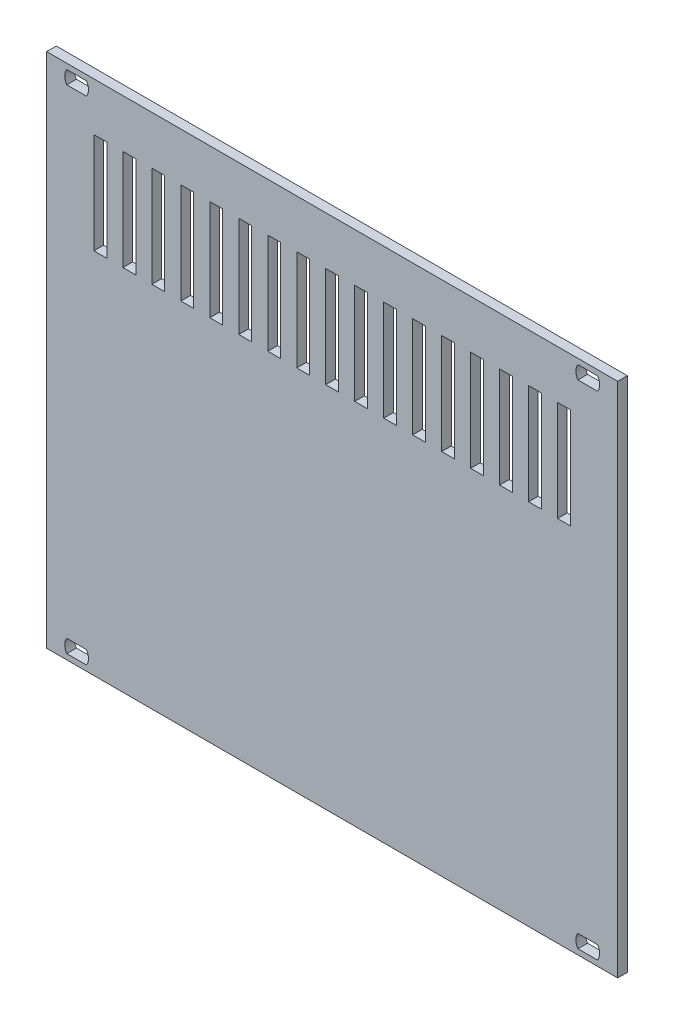
SolidWorks part; units mm, degrees
material "Alliage 1060"
ref_plane "Plan de face" through (0, 0, 0) normal (0, 0, 1) x (1, 0, 0)
ref_plane "Plan de dessus" through (0, 0, 0) normal (0, 1, 0) x (1, 0, 0)
ref_plane "Plan de droite" through (0, 0, 0) normal (1, 0, 0) x (0, 0, -1)
sketch "Model" plane through (0, 0, 0) normal (0, 0, 1) x (1, 0, 0)
  line L0 (141.9, 128.4) -> (141.9, 0)
  line L1 (0, 128.4) -> (141.9, 128.4)
  line L2 (0, 0) -> (0, 128.4)
  line L3 (141.9, 0) -> (0, 0)
  line L4 (9.8954, 123.75) -> (5.0046, 123.75)
  line L5 (5.0046, 127.05) -> (9.8954, 127.05)
  line L6 (9.8954, 1.35) -> (5.0046, 1.35)
  line L7 (5.0046, 4.65) -> (9.8954, 4.65)
  line L8 (136.8954, 123.75) -> (132.0046, 123.75)
  line L9 (132.0046, 127.05) -> (136.8954, 127.05)
  line L10 (136.8954, 1.35) -> (132.0046, 1.35)
  line L11 (132.0046, 4.65) -> (136.8954, 4.65)
  line L12 (14.95, 116.4) -> (14.95, 91.4)
  line L13 (14.95, 91.4) -> (11.75, 91.4)
  line L14 (11.75, 91.4) -> (11.75, 116.4)
  line L15 (11.75, 116.4) -> (14.95, 116.4)
  line L16 (22.15, 116.4) -> (22.15, 91.4)
  line L17 (22.15, 91.4) -> (18.95, 91.4)
  line L18 (18.95, 91.4) -> (18.95, 116.4)
  line L19 (18.95, 116.4) -> (22.15, 116.4)
  line L20 (29.35, 116.4) -> (29.35, 91.4)
  line L21 (29.35, 91.4) -> (26.15, 91.4)
  line L22 (26.15, 91.4) -> (26.15, 116.4)
  line L23 (26.15, 116.4) -> (29.35, 116.4)
  line L24 (36.55, 116.4) -> (36.55, 91.4)
  line L25 (36.55, 91.4) -> (33.35, 91.4)
  line L26 (33.35, 91.4) -> (33.35, 116.4)
  line L27 (33.35, 116.4) -> (36.55, 116.4)
  line L28 (43.75, 116.4) -> (43.75, 91.4)
  line L29 (43.75, 91.4) -> (40.55, 91.4)
  line L30 (40.55, 91.4) -> (40.55, 116.4)
  line L31 (40.55, 116.4) -> (43.75, 116.4)
  line L32 (50.95, 116.4) -> (50.95, 91.4)
  line L33 (50.95, 91.4) -> (47.75, 91.4)
  line L34 (47.75, 91.4) -> (47.75, 116.4)
  line L35 (47.75, 116.4) -> (50.95, 116.4)
  line L36 (58.15, 116.4) -> (58.15, 91.4)
  line L37 (58.15, 91.4) -> (54.95, 91.4)
  line L38 (54.95, 91.4) -> (54.95, 116.4)
  line L39 (54.95, 116.4) -> (58.15, 116.4)
  line L40 (65.35, 116.4) -> (65.35, 91.4)
  line L41 (65.35, 91.4) -> (62.15, 91.4)
  line L42 (62.15, 91.4) -> (62.15, 116.4)
  line L43 (62.15, 116.4) -> (65.35, 116.4)
  line L44 (72.55, 116.4) -> (72.55, 91.4)
  line L45 (72.55, 91.4) -> (69.35, 91.4)
  line L46 (69.35, 91.4) -> (69.35, 116.4)
  line L47 (69.35, 116.4) -> (72.55, 116.4)
  line L48 (79.75, 116.4) -> (79.75, 91.4)
  line L49 (79.75, 91.4) -> (76.55, 91.4)
  line L50 (76.55, 91.4) -> (76.55, 116.4)
  line L51 (76.55, 116.4) -> (79.75, 116.4)
  line L52 (86.95, 116.4) -> (86.95, 91.4)
  line L53 (86.95, 91.4) -> (83.75, 91.4)
  line L54 (83.75, 91.4) -> (83.75, 116.4)
  line L55 (83.75, 116.4) -> (86.95, 116.4)
  line L56 (94.15, 116.4) -> (94.15, 91.4)
  line L57 (94.15, 91.4) -> (90.95, 91.4)
  line L58 (90.95, 91.4) -> (90.95, 116.4)
  line L59 (90.95, 116.4) -> (94.15, 116.4)
  line L60 (101.35, 116.4) -> (101.35, 91.4)
  line L61 (101.35, 91.4) -> (98.15, 91.4)
  line L62 (98.15, 91.4) -> (98.15, 116.4)
  line L63 (98.15, 116.4) -> (101.35, 116.4)
  line L64 (108.55, 116.4) -> (108.55, 91.4)
  line L65 (108.55, 91.4) -> (105.35, 91.4)
  line L66 (105.35, 91.4) -> (105.35, 116.4)
  line L67 (105.35, 116.4) -> (108.55, 116.4)
  line L68 (115.75, 116.4) -> (115.75, 91.4)
  line L69 (115.75, 91.4) -> (112.55, 91.4)
  line L70 (112.55, 91.4) -> (112.55, 116.4)
  line L71 (112.55, 116.4) -> (115.75, 116.4)
  line L72 (122.95, 116.4) -> (122.95, 91.4)
  line L73 (122.95, 91.4) -> (119.75, 91.4)
  line L74 (119.75, 91.4) -> (119.75, 116.4)
  line L75 (119.75, 116.4) -> (122.95, 116.4)
  line L76 (130.15, 116.4) -> (130.15, 91.4)
  line L77 (130.15, 91.4) -> (126.95, 91.4)
  line L78 (126.95, 91.4) -> (126.95, 116.4)
  line L79 (126.95, 116.4) -> (130.15, 116.4)
  arc A0 (5.0046, 127.05) -> (5.0046, 123.75) centre (7.45, 125.4) ccw
  arc A1 (9.8954, 123.75) -> (9.8954, 127.05) centre (7.45, 125.4) ccw
  arc A2 (5.0046, 4.65) -> (5.0046, 1.35) centre (7.45, 3) ccw
  arc A3 (9.8954, 1.35) -> (9.8954, 4.65) centre (7.45, 3) ccw
  arc A4 (132.0046, 127.05) -> (132.0046, 123.75) centre (134.45, 125.4) ccw
  arc A5 (136.8954, 123.75) -> (136.8954, 127.05) centre (134.45, 125.4) ccw
  arc A6 (132.0046, 4.65) -> (132.0046, 1.35) centre (134.45, 3) ccw
  arc A7 (136.8954, 1.35) -> (136.8954, 4.65) centre (134.45, 3) ccw
extrude "Boss.-Extru.1" add sketch "Model" along normal blind 2.4
